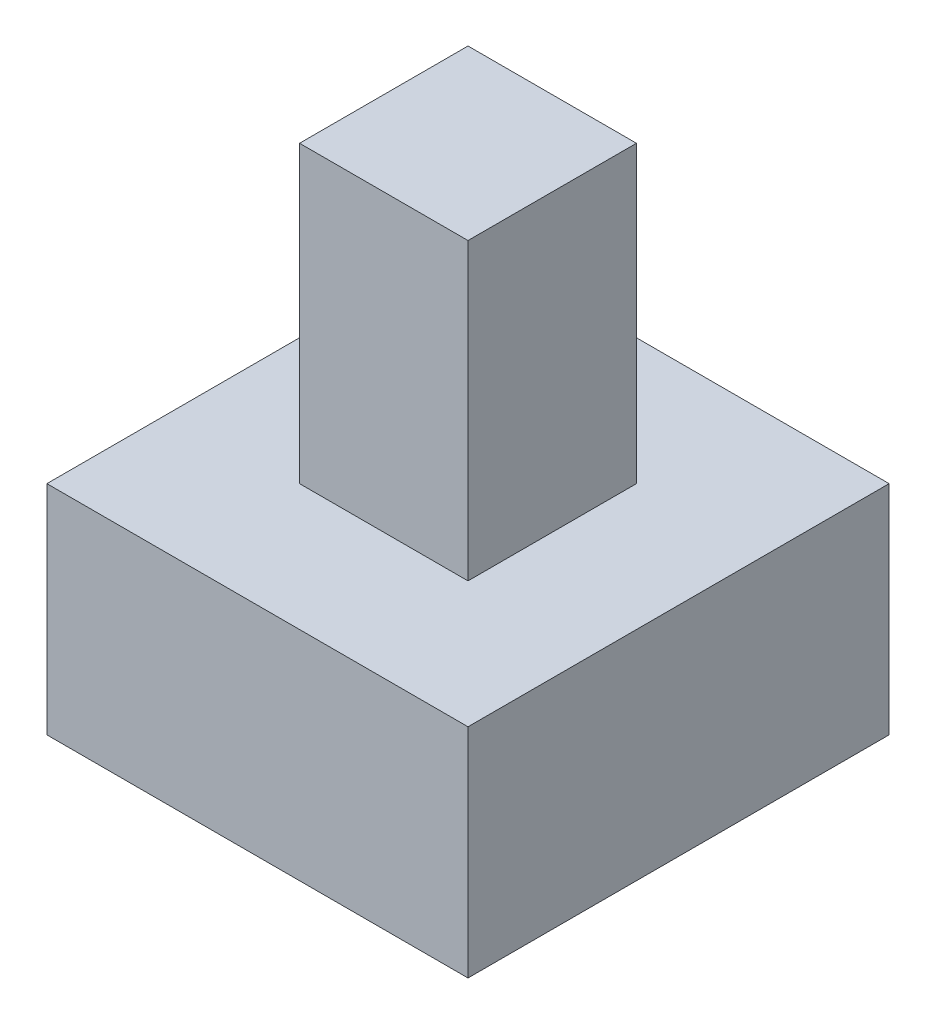
SolidWorks part; units mm, degrees
ref_plane "前视" through (0, 0, 0) normal (0, 0, 1) x (1, 0, 0)
ref_plane "上视" through (0, 0, 0) normal (0, 1, 0) x (1, 0, 0)
ref_plane "右视" through (0, 0, 0) normal (1, 0, 0) x (0, 0, -1)
sketch "草图1" plane through (0, 0, 0) normal (0, 1, 0) x (1, 0, 0)
  line L0 (0, 96.9306) -> (0, -101.3275) construction
  line L1 (-119.7143, 0) -> (134.9034, 0) construction
  line L3 (-3, 3) -> (3, 3)
  line L4 (-3, 3) -> (-3, -3)
  line L5 (-3, -3) -> (3, -3)
  line L6 (3, 3) -> (3, -3)
  dimension "D1" = 6
  dimension "D2" = 6
extrude "拉伸1" add sketch "草图1" along normal blind 3.1
sketch "草图2" plane through (0, 3.1, 0) normal (0, 1, 0) x (-1, 0, 0)
  line L0 (-3, 0) -> (8.7109, 0) construction
  line L1 (-3, 3) -> (-3, -3) construction
  line L3 (0, 4.4308) -> (0, -5.1525) construction
  line L4 (-1.2, 1.2) -> (1.2, 1.2)
  line L5 (-1.2, 1.2) -> (-1.2, -1.2)
  line L6 (-1.2, -1.2) -> (1.2, -1.2)
  line L7 (1.2, 1.2) -> (1.2, -1.2)
  dimension "D1" = 2.4
  dimension "D2" = 2.4
extrude "拉伸2" add sketch "草图2" along normal offset from surface (4.2 mm away) 7.3 up to face at (0, 0, 0)
sketch "草图3" plane through (-3, 0, 0) normal (-1, 0, 0) x (0, 0, 1)
  line L0 (0, -6.9925) -> (0, 14.8526) construction
sketch "草图4" plane through (0, 7.3, 0) normal (0, 1, 0) x (-1, 0, 0)
  line L0 (0, -4.1469) -> (0, 4.9476) construction
  line L1 (-3.9082, 0) -> (5.1305, 0) construction
sketch "草图5" plane through (0, 0, 0) normal (0, -1, 0) x (1, 0, 0)
  line L0 (-4.4583, 0) -> (4.1341, 0) construction
  line L1 (0, 4.6756) -> (0, -4.3899) construction
